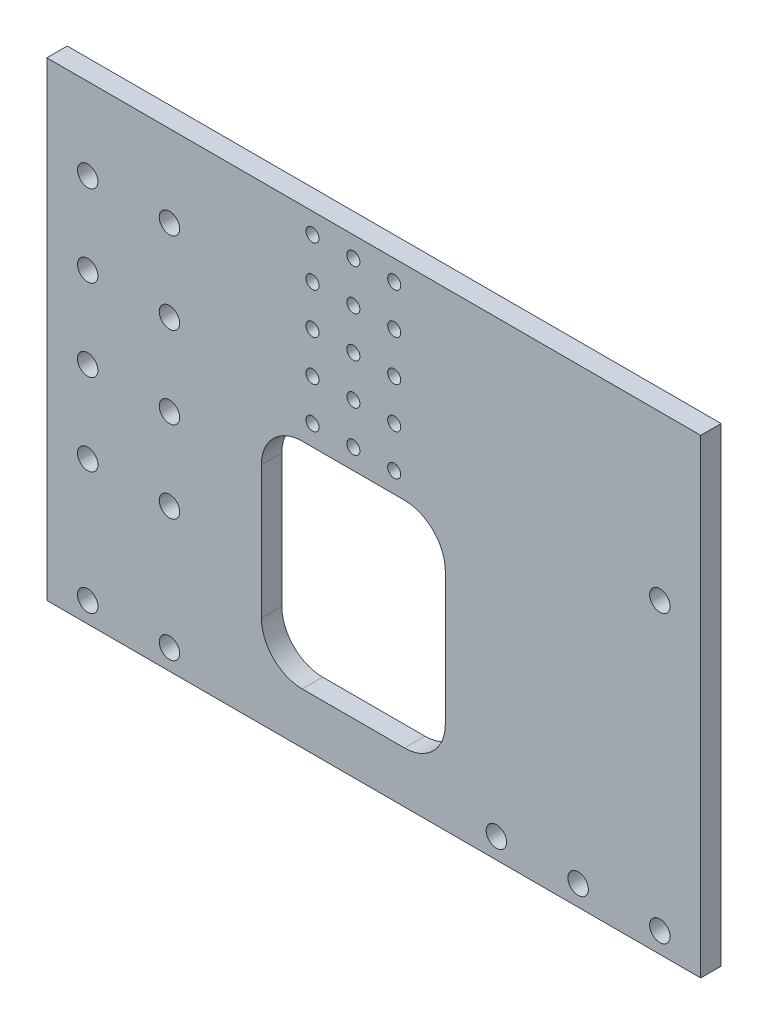
SolidWorks part; units mm, degrees
ref_plane "Front Plane" through (0, 0, 0) normal (0, 0, 1) x (1, 0, 0)
ref_plane "Top Plane" through (0, 0, 0) normal (0, 1, 0) x (1, 0, 0)
ref_plane "Right Plane" through (0, 0, 0) normal (1, 0, 0) x (0, 0, -1)
sketch "Sketch1" plane through (0, 0, 0) normal (0, 0, 1) x (1, 0, 0)
  line L1 (0, 0) -> (203.2, 0)
  line L2 (0, 0) -> (0, 146.05)
  line L3 (0, 146.05) -> (203.2, 146.05)
  line L4 (203.2, 0) -> (203.2, 146.05)
  dimension "D1" = 146.05
  dimension "D2" = 203.2
extrude "Boss-Extrude1" add sketch "Sketch1" along normal blind 6.35
sketch "Sketch2" plane through (0, 0, 6.35) normal (0, 0, 1) x (1, 0, 0)
  line L0 (0, 0) -> (203.2, 0) construction
  line L1 (12.7, 6.35) -> (38.1, 6.35) construction
  line L2 (12.7, 6.35) -> (12.7, 95.25) construction
  line L3 (12.7, 95.25) -> (38.1, 95.25) construction
  line L4 (38.1, 6.35) -> (38.1, 95.25) construction
  line L5 (0, 146.05) -> (0, 0) construction
  line L6 (38.1, 95.25) -> (190.5, 95.25) construction
  line L7 (38.1, 6.35) -> (190.5, 6.35) construction
  line L8 (190.5, 6.35) -> (190.5, 95.25) construction
  line L9 (203.2, 0) -> (203.2, 146.05) construction
  line L10 (12.7, 120.65) -> (12.7, 95.25) construction
  line L11 (12.7, 95.25) -> (12.7, 69.85) construction
  circle A0 centre (12.7, 6.35) radius 3.175
  circle A1 centre (38.1, 6.35) radius 3.175
  circle A2 centre (12.7, 95.25) radius 3.175
  circle A3 centre (38.1, 95.25) radius 3.175
  circle A4 centre (190.5, 95.25) radius 3.175
  circle A5 centre (190.5, 6.35) radius 3.175
  circle A6 centre (12.7, 69.85) radius 3.175
  circle A7 centre (38.1, 69.85) radius 3.175
  circle A8 centre (12.7, 44.45) radius 3.175
  circle A9 centre (38.1, 44.45) radius 3.175
  circle A10 centre (12.7, 120.65) radius 3.175
  circle A11 centre (38.1, 120.65) radius 3.175
  circle A12 centre (165.1, 6.35) radius 3.175
  circle A13 centre (139.7, 6.35) radius 3.175
  point P34 (144.2452, 6.35)
  dimension "D2" = 6.35
  dimension "D1" = 6.35
  dimension "D3" = 12.7
  dimension "D4" = 88.9
  dimension "D5" = 25.4
  dimension "D6" = 12.7
  dimension "D9" = 25.4
  dimension "D10" = 25.4
  dimension "D11" = 25.4
  dimension "D7" = 3
  dimension "D8" = 2
extrude "Cut-Extrude1" cut sketch "Sketch2" against normal through all both and the other way through all
sketch "Sketch3" plane through (0, 0, 6.35) normal (0, 0, 1) x (1, 0, 0)
  line L0 (82.55, 139.7) -> (107.95, 139.7) construction
  line L1 (82.55, 139.7) -> (82.55, 127) construction
  line L2 (82.55, 127) -> (107.95, 127) construction
  line L3 (107.95, 127) -> (107.95, 139.7) construction
  line L4 (0, 146.05) -> (0, 0) construction
  line L6 (203.2, 146.05) -> (0, 146.05) construction
  circle A0 centre (95.25, 139.7) radius 2.032
  circle A1 centre (107.95, 139.7) radius 2.032
  circle A2 centre (82.55, 139.7) radius 2.032
  circle A3 centre (107.95, 127) radius 2.032
  circle A4 centre (95.25, 127) radius 2.032
  circle A5 centre (82.55, 127) radius 2.032
  circle A6 centre (107.95, 114.3) radius 2.032
  circle A7 centre (95.25, 114.3) radius 2.032
  circle A8 centre (82.55, 114.3) radius 2.032
  circle A9 centre (107.95, 101.6) radius 2.032
  circle A10 centre (95.25, 101.6) radius 2.032
  circle A11 centre (82.55, 101.6) radius 2.032
  circle A12 centre (107.95, 88.9) radius 2.032
  circle A13 centre (95.25, 88.9) radius 2.032
  circle A14 centre (82.55, 88.9) radius 2.032
  point P9 (107.95, 113.5751)
  dimension "D4" = 4.064
  dimension "D1" = 25.4
  dimension "D2" = 95.25
  dimension "D3" = 6.35
  dimension "D5" = 12.7
  dimension "D6" = 5
extrude "Cut-Extrude2" cut sketch "Sketch3" against normal through all both and the other way through all
sketch "Sketch4" plane through (0, 0, 6.35) normal (0, 0, 1) x (1, 0, 0)
  line L1 (66.675, 82.55) -> (123.825, 82.55)
  line L2 (66.675, 82.55) -> (66.675, 15.875)
  line L3 (66.675, 15.875) -> (123.825, 15.875)
  line L4 (123.825, 82.55) -> (123.825, 15.875)
  line L5 (95.25, 101.6) -> (95.25, 82.55) construction
  circle A0 centre (107.95, 88.9) radius 2.032 construction
  dimension "D2" = 6.35
  dimension "D1" = 57.15
  dimension "D3" = 66.675
extrude "Cut-Extrude3" cut sketch "Sketch4" against normal through all both and the other way through all
fillet "Fillet1" radius 12.7 4 edges at (123.825, 82.55, 3.175) (66.675, 82.55, 3.175) (123.825, 15.875, 3.175) (66.675, 15.875, 3.175)
